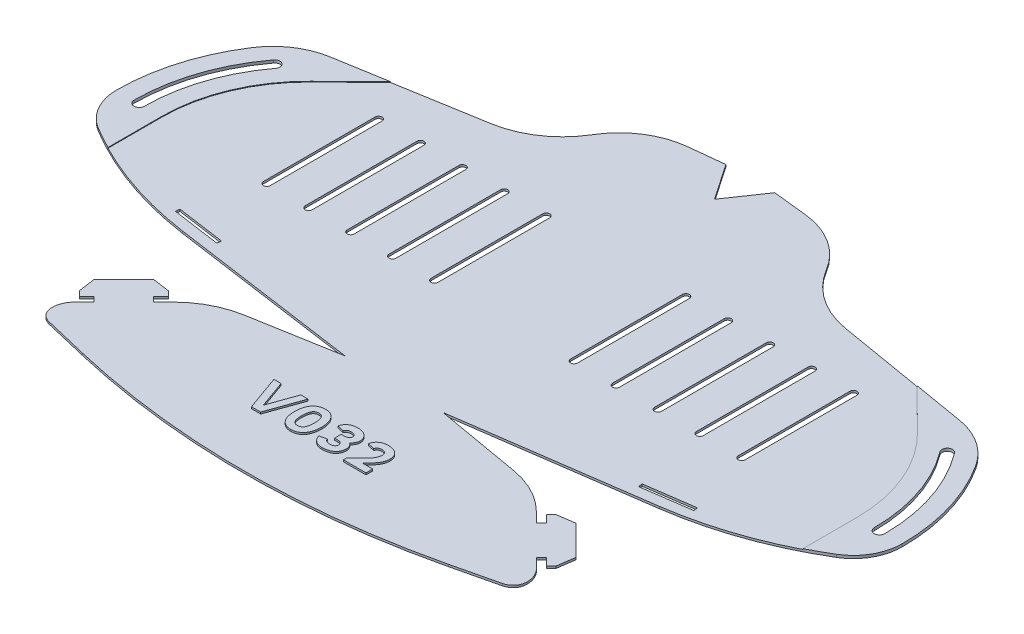
SolidWorks part; units mm, degrees
ref_plane "Front Plane" through (0, 0, 0) normal (0, 0, 1) x (1, 0, 0)
ref_plane "Top Plane" through (0, 0, 0) normal (0, 1, 0) x (1, 0, 0)
ref_plane "Right Plane" through (0, 0, 0) normal (1, 0, 0) x (0, 0, -1)
sketch "Sketch1" plane through (0, 0, 0) normal (0, 1, 0) x (1, 0, 0)
  line L0 (0, 0) -> (0, -145) construction
  line L1 (-14, -102) -> (14, -102) construction
  line L2 (-112.5, -69) -> (112.5, -69) construction
  line L3 (0, -10.2352) -> (-7, 0)
  line L4 (0, -10.2352) -> (7, 0)
  line L5 (7, 0) -> (16.9419, -1.0768)
  line L6 (-90.1804, -30.1909) -> (-50.7439, -23.5)
  line L7 (90.1804, -30.1909) -> (50.7439, -23.5)
  line L8 (-14, -102) -> (-68.2662, -94.2919)
  line L9 (-7, 0) -> (-16.9419, -1.0768)
  line L10 (14, -102) -> (68.2662, -94.2919)
  line L11 (-103.5977, -39) -> (-103.5977, -69) construction
  line L12 (-14, -102) -> (-38.6266, -106.305)
  line L13 (-52, -113.2546) -> (-54.8283, -116.0832)
  line L14 (52, -113.2546) -> (54.8283, -116.0832)
  line L15 (14, -102) -> (38.6266, -106.305)
  line L16 (-54.8283, -116.0832) -> (-56.2426, -114.669)
  line L17 (-56.2426, -114.669) -> (-54.1214, -112.5476)
  line L18 (-54.1214, -112.5476) -> (-55.5356, -111.1334)
  line L19 (-55.5356, -111.1334) -> (-60.4854, -110.4265)
  line L20 (-60.4854, -110.4265) -> (-68.9703, -118.9122)
  line L21 (-64.7275, -123.1546) -> (-63.3132, -124.5688)
  line L22 (-63.3132, -124.5688) -> (-66.1415, -127.3973)
  line L23 (-64.7275, -123.1546) -> (-66.8487, -125.2761)
  line L24 (-66.8487, -125.2761) -> (-68.263, -123.8619)
  line L25 (-68.9703, -118.9122) -> (-68.263, -123.8619)
  line L26 (68.9703, -118.9122) -> (68.263, -123.8619)
  line L27 (66.8487, -125.2761) -> (68.263, -123.8619)
  line L28 (64.7275, -123.1546) -> (66.8487, -125.2761)
  line L29 (63.3132, -124.5688) -> (66.1415, -127.3973)
  line L30 (64.7275, -123.1546) -> (63.3132, -124.5688)
  line L31 (60.4854, -110.4265) -> (68.9703, -118.9122)
  line L32 (55.5356, -111.1334) -> (60.4854, -110.4265)
  line L33 (54.1214, -112.5476) -> (55.5356, -111.1334)
  line L34 (56.2426, -114.669) -> (54.1214, -112.5476)
  line L35 (54.8283, -116.0832) -> (56.2426, -114.669)
  line L36 (-64.9691, -135.8852) -> (-52.4361, -138.8607)
  line L37 (64.9691, -135.8852) -> (52.4361, -138.8607)
  line L38 (-68.9703, -118.9122) -> (-64.7275, -123.1546) construction
  line L39 (-60.4854, -110.4265) -> (-56.2426, -114.669) construction
  arc A0 (-16.9419, -1.0768) -> (-33.4614, -11.6696) centre (-14.5729, -22.9489) ccw
  arc A1 (-33.4614, -11.6696) -> (-50.7439, -23.5) centre (-54.9257, 1.1478) cw
  arc A2 (-103.5977, -39) -> (-90.1804, -30.1909) centre (-86.8349, -49.9091) cw
  arc A3 (-112.5, -69) -> (-103.5977, -39) centre (-57.5, -69) cw
  arc A4 (112.5, -69) -> (103.5977, -39) centre (57.5, -69) ccw
  arc A5 (103.5977, -39) -> (90.1804, -30.1909) centre (86.8349, -49.9091) ccw
  arc A6 (16.9419, -1.0768) -> (33.4614, -11.6696) centre (14.5729, -22.9489) cw
  arc A7 (33.4614, -11.6696) -> (50.7439, -23.5) centre (54.9257, 1.1478) ccw
  arc A8 (-112.5, -69) -> (-105.7111, -81) centre (-98.5, -69) ccw
  arc A9 (-105.7111, -81) -> (-68.2662, -94.2919) centre (-54.2032, 4.7143) ccw
  arc A10 (112.5, -69) -> (105.7111, -81) centre (98.5, -69) cw
  arc A11 (105.7111, -81) -> (68.2662, -94.2919) centre (54.2032, 4.7143) cw
  arc A12 (-38.6266, -106.305) -> (-52, -113.2546) centre (-34.3216, -130.9315) ccw
  arc A13 (38.6266, -106.305) -> (52, -113.2546) centre (34.3216, -130.9315) cw
  arc A14 (-66.1415, -127.3973) -> (-68.0451, -131.9933) centre (-61.5451, -131.9933) ccw
  arc A15 (-68.0451, -131.9933) -> (-64.9691, -135.8852) centre (-64.0451, -131.9933) ccw
  arc A16 (68.0451, -131.9933) -> (64.9691, -135.8852) centre (64.0451, -131.9933) cw
  arc A17 (66.1415, -127.3973) -> (68.0451, -131.9933) centre (61.5451, -131.9933) cw
  arc A19 (-52.4361, -138.8607) -> (0, -145) centre (0, 82) ccw
  arc A20 (52.4361, -138.8607) -> (0, -145) centre (0, 82) cw
  point P8 (0, -102)
  point P11 (0, -69)
  dimension "D5" = 55
  dimension "D11" = 20
  dimension "D13" = 25
  dimension "D16" = 14
  dimension "D15" = 22
  dimension "D18" = 100
  dimension "D22" = 25
  dimension "D31" = 6.5
  dimension "D32" = 4
  dimension "D34" = 227
  dimension "D1" = 145
  dimension "D2" = 28
  dimension "D3" = 43
  dimension "D4" = 76
  dimension "D6" = 225
  dimension "D7" = 14
  dimension "D8" = 12.4
  dimension "D9" = 10
  dimension "D10" = 30
  dimension "D12" = 40
  dimension "D14" = 45.5
  dimension "D17" = 12
  dimension "D19" = 18
  dimension "D20" = 25
  dimension "D21" = 4
  dimension "D23" = 38
  dimension "D24" = 2
  dimension "D25" = 3
  dimension "D26" = 2
  dimension "D27" = 18
  dimension "D29" = 8
  dimension "D30" = 4
extrude "Main Shape" add sketch "Sketch1" along normal blind 0.6
sketch "Sketch2" plane through (0, 0.6, 0) normal (0, 1, 0) x (1, 0, 0)
  line L0 (0, -55) -> (0, 55) construction
  arc A0 (-96.3, -39.9) -> (-106, -69) centre (-57.5, -69) ccw construction
  arc A1 (-97.5, -39) -> (-107.5, -69) centre (-57.5, -69) ccw
  arc A2 (-95.1, -40.8) -> (-104.5, -69) centre (-57.5, -69) ccw
  arc A3 (-95.1, -40.8) -> (-97.5, -39) centre (-96.3, -39.9) ccw
  arc A4 (-107.5, -69) -> (-104.5, -69) centre (-106, -69) ccw
  arc A6 (-103.5977, -39) -> (-112.5, -69) centre (-57.5, -69) ccw construction
  arc A7 (96.3, -39.9) -> (106, -69) centre (57.5, -69) cw construction
  arc A8 (97.5, -39) -> (107.5, -69) centre (57.5, -69) cw
  arc A9 (95.1, -40.8) -> (104.5, -69) centre (57.5, -69) cw
  arc A10 (95.1, -40.8) -> (97.5, -39) centre (96.3, -39.9) cw
  arc A11 (107.5, -69) -> (104.5, -69) centre (106, -69) cw
  point P3 (-103.5111, -53.663)
  point P19 (103.5111, -53.663)
  dimension "D1" = 5
  dimension "D2" = 1.5
extrude "Elastic Attachment Points" cut sketch "Sketch2" against normal through all
sketch "Sketch7" plane through (0, 0.6, 0) normal (0, 1, 0) x (1, 0, 0)
  line L0 (-99.5, -69) -> (-99.5, -84.4384)
  line L1 (-86.8939, -39) -> (-75.3319, -27.6717)
  line L2 (-50.7439, -23.5) -> (-90.1804, -30.1909) construction
  line L3 (-75.3319, -27.6717) -> (-90.1804, -30.1909)
  line L4 (0, -55) -> (0, 55) construction
  line L5 (75.3319, -27.6717) -> (90.1804, -30.1909)
  line L6 (86.8939, -39) -> (75.3319, -27.6717)
  line L7 (99.5, -69) -> (99.5, -84.4384)
  arc A0 (-99.5, -69) -> (-86.8939, -39) centre (-57.5, -69) cw
  arc A1 (-95.1, -40.8) -> (-104.5, -69) centre (-57.5, -69) ccw construction
  arc A2 (-105.7111, -81) -> (-68.2662, -94.2919) centre (-54.2032, 4.7143) ccw construction
  arc A3 (-112.5, -69) -> (-105.7111, -81) centre (-98.5, -69) ccw construction
  arc A4 (-103.5977, -39) -> (-112.5, -69) centre (-57.5, -69) ccw construction
  arc A5 (-90.1804, -30.1909) -> (-103.5977, -39) centre (-86.8349, -49.9091) ccw construction
  arc A6 (-105.7111, -81) -> (-99.5, -84.4384) centre (-54.2032, 4.7143) ccw
  arc A7 (-112.5, -69) -> (-105.7111, -81) centre (-98.5, -69) ccw
  arc A8 (-103.5977, -39) -> (-112.5, -69) centre (-57.5, -69) ccw
  arc A9 (-90.1804, -30.1909) -> (-103.5977, -39) centre (-86.8349, -49.9091) ccw
  arc A10 (90.1804, -30.1909) -> (103.5977, -39) centre (86.8349, -49.9091) cw
  arc A11 (103.5977, -39) -> (112.5, -69) centre (57.5, -69) cw
  arc A12 (112.5, -69) -> (105.7111, -81) centre (98.5, -69) cw
  arc A13 (105.7111, -81) -> (99.5, -84.4384) centre (54.2032, 4.7143) cw
  arc A14 (99.5, -69) -> (86.8939, -39) centre (57.5, -69) ccw
  arc A15 (-107.5, -69) -> (-104.5, -69) centre (-106, -69) ccw construction
  arc A16 (-95.1, -40.8) -> (-97.5, -39) centre (-96.3, -39.9) ccw construction
  arc A17 (-97.5, -39) -> (-107.5, -69) centre (-57.5, -69) ccw construction
  arc A18 (-107.5, -69) -> (-104.5, -69) centre (-106, -69) ccw
  arc A19 (-95.1, -40.8) -> (-97.5, -39) centre (-96.3, -39.9) ccw
  arc A20 (-95.1, -40.8) -> (-104.5, -69) centre (-57.5, -69) ccw
  arc A21 (-97.5, -39) -> (-107.5, -69) centre (-57.5, -69) ccw
  arc A22 (104.5, -69) -> (107.5, -69) centre (106, -69) ccw construction
  arc A23 (97.5, -39) -> (95.1, -40.8) centre (96.3, -39.9) ccw construction
  arc A24 (104.5, -69) -> (95.1, -40.8) centre (57.5, -69) ccw construction
  arc A25 (107.5, -69) -> (97.5, -39) centre (57.5, -69) ccw construction
  arc A26 (104.5, -69) -> (107.5, -69) centre (106, -69) ccw
  arc A27 (97.5, -39) -> (95.1, -40.8) centre (96.3, -39.9) ccw
  arc A28 (104.5, -69) -> (95.1, -40.8) centre (57.5, -69) ccw
  arc A29 (107.5, -69) -> (97.5, -39) centre (57.5, -69) ccw
  dimension "D1" = 5
extrude "Reinforced Attachment Points" add sketch "Sketch7" along normal blind 0.2
sketch "Sketch6" plane through (0, 0.6, 0) normal (0, 1, 0) x (1, 0, 0)
  line L0 (-74.2491, -90.412) -> (-60.3883, -92.3808)
  line L1 (-60.3883, -92.3808) -> (-60.2195, -91.1927)
  line L2 (-60.2195, -91.1927) -> (-74.0804, -89.2239)
  line L3 (-74.0804, -89.2239) -> (-74.2491, -90.412)
  line L4 (-68.2662, -94.2919) -> (-14, -102) construction
  line L5 (-67.1499, -90.2083) -> (-67.3187, -91.3964) construction
  line L13 (0, -0.44) -> (0, 0.44) construction
  line L14 (67.1499, -90.2083) -> (67.3187, -91.3964) construction
  line L15 (74.2491, -90.412) -> (74.0804, -89.2239)
  line L16 (60.2195, -91.1927) -> (60.3883, -92.3808)
  line L22 (60.2195, -91.1927) -> (74.0804, -89.2239)
  line L24 (74.2491, -90.412) -> (60.3883, -92.3808)
  dimension "D1" = 3
  dimension "D2" = 14
  dimension "D3" = 54.28
  dimension "D4" = 1.2
extrude "Tab Slits" cut sketch "Sketch6" against normal through all
sketch "Sketch3" plane through (0, 0.6, 0) normal (0, 1, 0) x (1, 0, 0)
  line L0 (-20, -38.45) -> (-20, -70.45) construction
  line L1 (-19, -38.45) -> (-19, -70.45)
  line L2 (-21, -38.45) -> (-21, -70.45)
  line L3 (0, -10.2352) -> (0, -145) construction
  line L4 (-106, -69) -> (-96.3, -69) construction
  line L5 (-96.3, -69) -> (-96.3, -39.9) construction
  line L6 (-32, -38.45) -> (-32, -70.45) construction
  line L7 (-31, -38.45) -> (-31, -70.45)
  line L8 (-33, -38.45) -> (-33, -70.45)
  line L9 (-44, -38.45) -> (-44, -70.45) construction
  line L10 (-43, -38.45) -> (-43, -70.45)
  line L11 (-45, -38.45) -> (-45, -70.45)
  line L12 (-56, -38.45) -> (-56, -70.45) construction
  line L13 (-55, -38.45) -> (-55, -70.45)
  line L14 (-57, -38.45) -> (-57, -70.45)
  line L15 (-68, -38.45) -> (-68, -70.45) construction
  line L16 (-67, -38.45) -> (-67, -70.45)
  line L17 (-69, -38.45) -> (-69, -70.45)
  line L18 (20, -38.45) -> (20, -70.45) construction
  line L19 (19, -38.45) -> (19, -70.45)
  line L20 (21, -38.45) -> (21, -70.45)
  line L21 (32, -38.45) -> (32, -70.45) construction
  line L22 (31, -38.45) -> (31, -70.45)
  line L23 (33, -38.45) -> (33, -70.45)
  line L24 (44, -38.45) -> (44, -70.45) construction
  line L25 (43, -38.45) -> (43, -70.45)
  line L26 (45, -38.45) -> (45, -70.45)
  line L27 (56, -38.45) -> (56, -70.45) construction
  line L28 (55, -38.45) -> (55, -70.45)
  line L29 (57, -38.45) -> (57, -70.45)
  line L30 (68, -38.45) -> (68, -70.45) construction
  line L31 (67, -38.45) -> (67, -70.45)
  line L32 (69, -38.45) -> (69, -70.45)
  arc A0 (-19, -38.45) -> (-21, -38.45) centre (-20, -38.45) ccw
  arc A1 (-21, -70.45) -> (-19, -70.45) centre (-20, -70.45) ccw
  arc A2 (-52.4361, -138.8607) -> (52.4361, -138.8607) centre (0, 82) ccw construction
  arc A3 (-31, -38.45) -> (-33, -38.45) centre (-32, -38.45) ccw
  arc A4 (-33, -70.45) -> (-31, -70.45) centre (-32, -70.45) ccw
  arc A5 (-43, -38.45) -> (-45, -38.45) centre (-44, -38.45) ccw
  arc A6 (-45, -70.45) -> (-43, -70.45) centre (-44, -70.45) ccw
  arc A7 (-55, -38.45) -> (-57, -38.45) centre (-56, -38.45) ccw
  arc A8 (-57, -70.45) -> (-55, -70.45) centre (-56, -70.45) ccw
  arc A9 (-67, -38.45) -> (-69, -38.45) centre (-68, -38.45) ccw
  arc A10 (-69, -70.45) -> (-67, -70.45) centre (-68, -70.45) ccw
  arc A11 (19, -38.45) -> (21, -38.45) centre (20, -38.45) cw
  arc A12 (21, -70.45) -> (19, -70.45) centre (20, -70.45) cw
  arc A13 (31, -38.45) -> (33, -38.45) centre (32, -38.45) cw
  arc A14 (33, -70.45) -> (31, -70.45) centre (32, -70.45) cw
  arc A15 (43, -38.45) -> (45, -38.45) centre (44, -38.45) cw
  arc A16 (45, -70.45) -> (43, -70.45) centre (44, -70.45) cw
  arc A17 (55, -38.45) -> (57, -38.45) centre (56, -38.45) cw
  arc A18 (57, -70.45) -> (55, -70.45) centre (56, -70.45) cw
  arc A19 (67, -38.45) -> (69, -38.45) centre (68, -38.45) cw
  arc A20 (69, -70.45) -> (67, -70.45) centre (68, -70.45) cw
  point P2 (-20, -54.45)
  point P13 (-19, -54.45)
  point P16 (-96.3, -54.45)
  point P20 (-32, -54.45)
  point P31 (-44, -54.45)
  point P38 (-56, -54.45)
  point P45 (-68, -54.45)
  point P52 (20, -54.45)
  point P59 (32, -54.45)
  point P66 (44, -54.45)
  point P73 (56, -54.45)
  point P80 (68, -54.45)
  dimension "D1" = 2
  dimension "D2" = 32
  dimension "D3" = 20
  dimension "D4" = 5
  dimension "D5" = 10
extrude "Breathing Slits" cut sketch "Sketch3" against normal through all
sketch "Sketch8" plane through (0, 0.6, 0) normal (0, 1, 0) x (1, 0, 0)
  line L0 (-67.0266, -128.5) -> (67.0266, -128.5) construction
  line L1 (0, -10.2352) -> (0, -145) construction
  arc A0 (-52.4361, -138.8607) -> (52.4361, -138.8607) centre (0, 82) ccw construction
  arc A1 (-66.1415, -127.3973) -> (-68.0451, -131.9933) centre (-61.5451, -131.9933) ccw construction
  text T0 "<b>V032</b>" font "Double Porter 3" height 10
  point P9 (0, -128.5)
  dimension "D2" = 16.5
extrude "Version Number" add sketch "Sketch8" along normal blind 0.5
